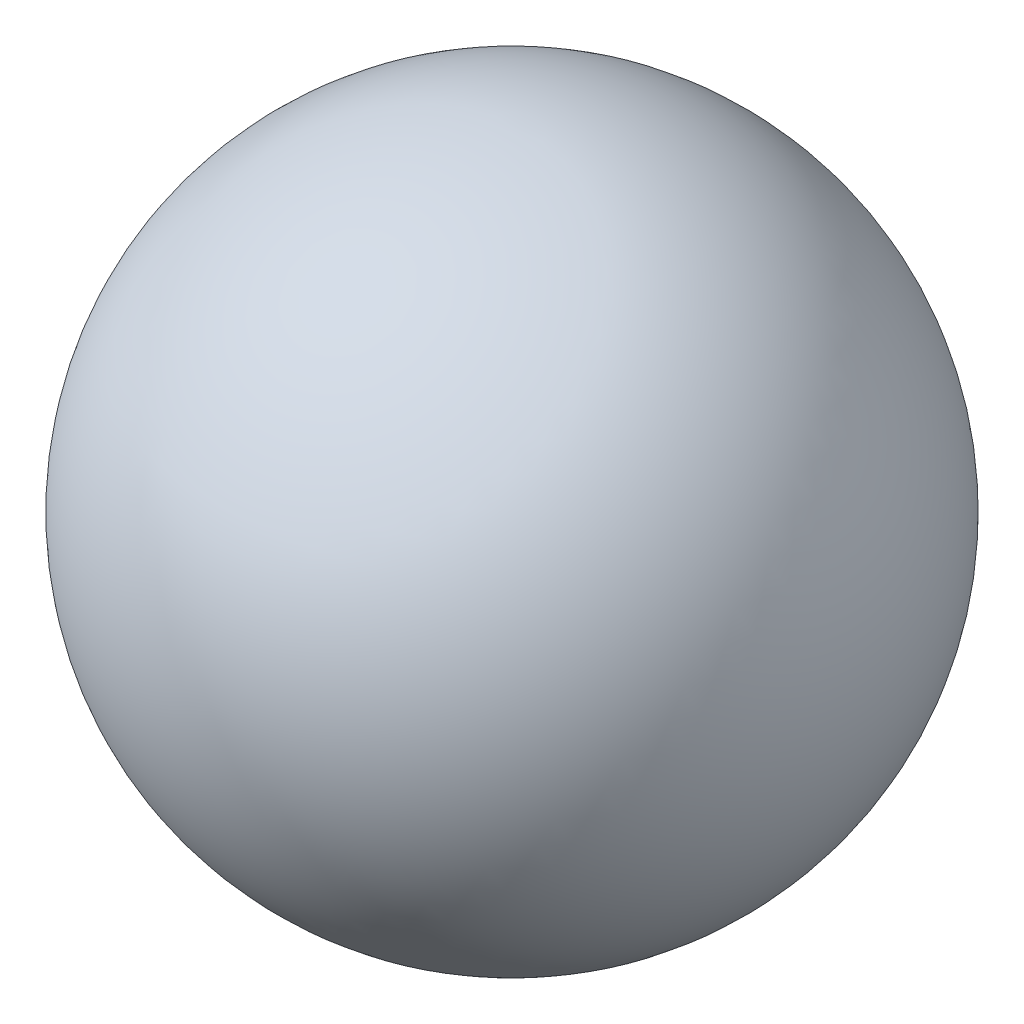
SolidWorks part; units mm, degrees
ref_plane "前视基准面" through (0, 0, 0) normal (0, 0, 1) x (1, 0, 0)
ref_plane "上视基准面" through (0, 0, 0) normal (0, 1, 0) x (1, 0, 0)
ref_plane "右视基准面" through (0, 0, 0) normal (1, 0, 0) x (0, 0, -1)
sketch "草图1" plane through (0, 0, 0) normal (0, 0, 1) x (1, 0, 0)
  line L0 (0, -21) -> (0, 21)
  arc A0 (0, -21) -> (0, 21) centre (0, 0) ccw
  dimension "D1" = 42
revolve "旋转1" add sketch "草图1" angle 360 about L0
